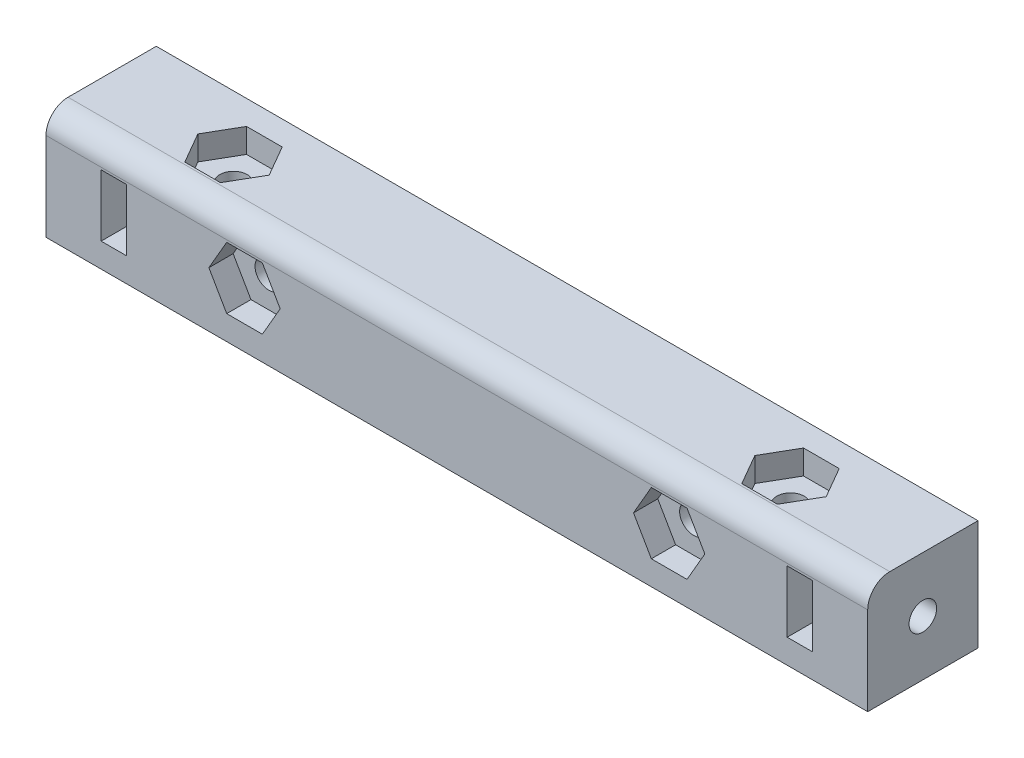
SolidWorks part; units mm, degrees
ref_plane "Front Plane" through (0, 0, 0) normal (0, 0, 1) x (1, 0, 0)
ref_plane "Top Plane" through (0, 0, 0) normal (0, 1, 0) x (1, 0, 0)
ref_plane "Right Plane" through (0, 0, 0) normal (1, 0, 0) x (0, 0, -1)
sketch "Sketch1" plane through (0, 0, 0) normal (0, 1, 0) x (1, 0, 0)
  line L1 (0, 0) -> (74.5, 0)
  line L2 (0, 0) -> (0, 10)
  line L3 (0, 10) -> (74.5, 10)
  line L4 (74.5, 0) -> (74.5, 10)
  dimension "D1" = 74.5
  dimension "D2" = 10
extrude "Boss-Extrude1" add sketch "Sketch1" along normal blind 10
sketch "Sketch2" plane through (0, 10, 0) normal (0, 1, 0) x (1, 0, 0)
  line L0 (0, 5) -> (74.5, 5) construction
  line L1 (0, 10) -> (0, 0) construction
  line L2 (74.5, 0) -> (74.5, 10) construction
  circle A0 centre (12, 5) radius 1.25
  circle A1 centre (62.5, 5) radius 1.25
  dimension "D3" = 2.5
  dimension "D4" = 2.5
  dimension "D1" = 12
  dimension "D2" = 12
extrude "Cut-Extrude1" cut sketch "Sketch2" against normal blind 10
sketch "Sketch3" plane through (0, 0, -10) normal (0, 0, -1) x (-1, 0, 0)
  line L0 (-74.5, 5) -> (0, 5) construction
  line L1 (-74.5, 10) -> (-74.5, 0) construction
  line L2 (0, 10) -> (0, 0) construction
  circle A0 centre (-56.5, 5) radius 1.25
  circle A1 centre (-18, 5) radius 1.25
  dimension "D1" = 2.5
  dimension "D2" = 2.5
  dimension "D3" = 18
  dimension "D4" = 18
extrude "Cut-Extrude2" cut sketch "Sketch3" against normal blind 10
sketch "Sketch4" plane through (74.5, 0, 0) normal (1, 0, 0) x (0, 0, -1)
  line L0 (5, 10) -> (5, 4.1725) construction
  line L1 (0, 10) -> (10, 10) construction
  line L2 (0, 5) -> (5.9702, 5) construction
  line L3 (0, 10) -> (0, 0) construction
  circle A0 centre (5, 5) radius 1.25
  dimension "D1" = 2.5
extrude "Cut-Extrude3" cut sketch "Sketch4" against normal blind 5
sketch "Sketch5" plane through (0, 0, 0) normal (-1, 0, 0) x (0, 0, 1)
  line L0 (-5, 10) -> (-5, 0) construction
  line L1 (-10, 10) -> (0, 10) construction
  line L2 (-10, 0) -> (0, 0) construction
  line L3 (-10, 5) -> (0, 5) construction
  line L4 (-10, 10) -> (-10, 0) construction
  line L5 (0, 10) -> (0, 0) construction
  circle A0 centre (-5, 5) radius 1.25
  dimension "D1" = 2.5
extrude "Cut-Extrude4" cut sketch "Sketch5" against normal blind 5
sketch "Sketch6" plane through (0, 10, 0) normal (0, 1, 0) x (1, 0, 0)
  line L0 (74.5, 10) -> (0, 10) construction
  line L1 (13.6166, 2.2) -> (15.2332, 5)
  line L2 (15.2332, 5) -> (13.6166, 7.8)
  line L3 (13.6166, 7.8) -> (10.3834, 7.8)
  line L4 (10.3834, 7.8) -> (8.7668, 5)
  line L5 (8.7668, 5) -> (10.3834, 2.2)
  line L6 (10.3834, 2.2) -> (13.6166, 2.2)
  circle A0 centre (12, 5) radius 2.8 construction
  dimension "D1" = 5.6
extrude "Cut-Extrude5" cut sketch "Sketch6" against normal blind 2.2
sketch "Sketch7" plane through (0, 10, 0) normal (0, 1, 0) x (1, 0, 0)
  line L0 (74.5, 10) -> (0, 10) construction
  line L1 (60.8834, 7.8) -> (59.2668, 5)
  line L2 (59.2668, 5) -> (60.8834, 2.2)
  line L3 (60.8834, 2.2) -> (64.1166, 2.2)
  line L4 (64.1166, 2.2) -> (65.7332, 5)
  line L5 (65.7332, 5) -> (64.1166, 7.8)
  line L6 (64.1166, 7.8) -> (60.8834, 7.8)
  circle A0 centre (62.5, 5) radius 2.8 construction
  dimension "D1" = 5.6
extrude "Cut-Extrude6" cut sketch "Sketch7" against normal blind 2.2
sketch "Sketch8" plane through (0, 0, 0) normal (0, 0, 1) x (1, 0, 0)
  line L0 (0, 10) -> (74.5, 10) construction
  line L1 (16.3834, 2.2) -> (19.6166, 2.2)
  line L2 (19.6166, 2.2) -> (21.2332, 5)
  line L3 (21.2332, 5) -> (19.6166, 7.8)
  line L4 (19.6166, 7.8) -> (16.3834, 7.8)
  line L5 (16.3834, 7.8) -> (14.7668, 5)
  line L6 (14.7668, 5) -> (16.3834, 2.2)
  circle A0 centre (18, 5) radius 2.8 construction
  dimension "D1" = 5.6
extrude "Cut-Extrude7" cut sketch "Sketch8" against normal blind 2.2
sketch "Sketch9" plane through (0, 0, 0) normal (0, 0, 1) x (1, 0, 0)
  line L1 (58.1166, 7.8) -> (54.8834, 7.8)
  line L2 (54.8834, 7.8) -> (53.2668, 5)
  line L3 (53.2668, 5) -> (54.8834, 2.2)
  line L4 (54.8834, 2.2) -> (58.1166, 2.2)
  line L5 (58.1166, 2.2) -> (59.7332, 5)
  line L6 (59.7332, 5) -> (58.1166, 7.8)
  circle A0 centre (56.5, 5) radius 2.8 construction
  dimension "D1" = 5.6
extrude "Cut-Extrude8" cut sketch "Sketch9" against normal blind 2.2
sketch "Sketch11" plane through (0, 0, 0) normal (0, 0, 1) x (1, 0, 0)
  line L0 (0, 5) -> (74.5, 5) construction
  line L1 (0, 10) -> (0, 0) construction
  line L2 (74.5, 10) -> (74.5, 0) construction
  line L4 (5, 2.2) -> (7.3, 2.2)
  line L5 (5, 2.2) -> (5, 7.8)
  line L6 (5, 7.8) -> (7.3, 7.8)
  line L7 (7.3, 2.2) -> (7.3, 7.8)
  line L8 (5, 2.2) -> (7.3, 7.8) construction
  line L9 (5, 7.8) -> (7.3, 2.2) construction
  line L10 (67.2, 2.2) -> (69.5, 2.2)
  line L11 (67.2, 2.2) -> (67.2, 7.8)
  line L12 (67.2, 7.8) -> (69.5, 7.8)
  line L13 (69.5, 2.2) -> (69.5, 7.8)
  line L14 (67.2, 2.2) -> (69.5, 7.8) construction
  line L15 (67.2, 7.8) -> (69.5, 2.2) construction
  point P6 (6.15, 5)
  point P11 (68.35, 5)
  dimension "D1" = 2.3
  dimension "D2" = 5.6
  dimension "D3" = 2.3
  dimension "D4" = 5.6
  dimension "D5" = 5
  dimension "D6" = 5
extrude "Cut-Extrude9" cut sketch "Sketch11" against normal blind 7.3
fillet "Fillet1" radius 2 1 edges at (37.25, 10, 0)
